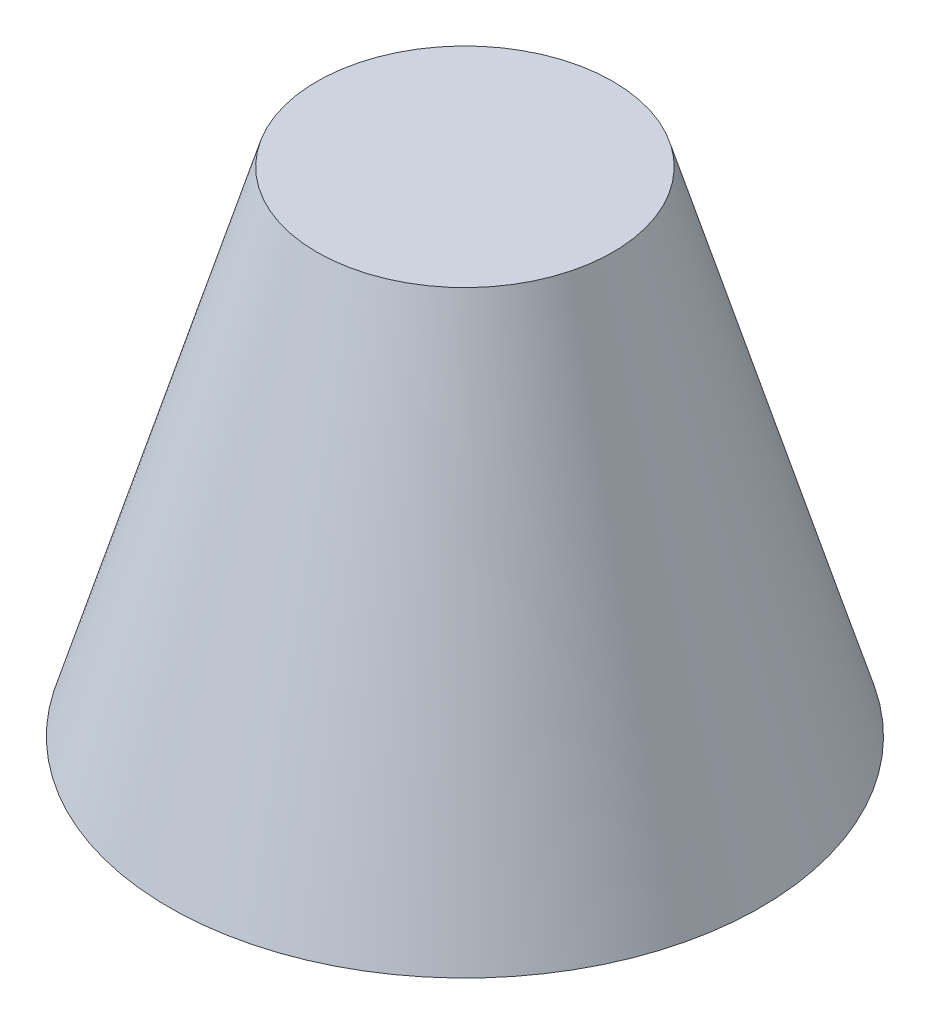
SolidWorks part; units mm, degrees
ref_plane "前视基准面" through (0, 0, 0) normal (0, 0, 1) x (1, 0, 0)
ref_plane "上视基准面" through (0, 0, 0) normal (0, 1, 0) x (1, 0, 0)
ref_plane "右视基准面" through (0, 0, 0) normal (1, 0, 0) x (0, 0, -1)
sketch "草图1" plane through (0, 0, 0) normal (0, 0, 1) x (1, 0, 0)
  line L0 (0, 0) -> (0, 25)
  line L1 (0, 25) -> (-7.5, 25)
  line L2 (-7.5, 25) -> (-15, 0)
  line L3 (-15, 0) -> (0, 0)
  dimension "D1" = 7.5
  dimension "D2" = 25
  dimension "D3" = 15
revolve "旋转1" add sketch "草图1" angle 360 about L0
